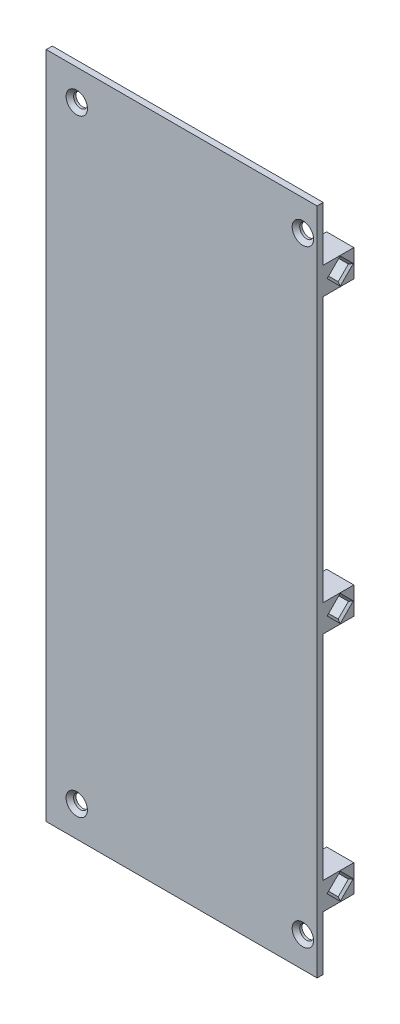
SolidWorks part; units mm, degrees
ref_plane "Front Plane" through (0, 0, 0) normal (0, 0, 1) x (1, 0, 0)
ref_plane "Top Plane" through (0, 0, 0) normal (0, 1, 0) x (1, 0, 0)
ref_plane "Right Plane" through (0, 0, 0) normal (1, 0, 0) x (0, 0, -1)
sketch "Sketch1" plane through (0, 0, 0) normal (0, 0, 1) x (1, 0, 0)
  line L1 (-42.2005, 104.14) -> (42.2005, 104.14)
  line L2 (-42.2005, 104.14) -> (-42.2005, -104.14)
  line L3 (-42.2005, -104.14) -> (42.2005, -104.14)
  line L4 (42.2005, 104.14) -> (42.2005, -104.14)
  point P4 (0, 104.14)
  point P6 (-42.2005, 0)
  dimension "D1" = 84.401
  dimension "D2" = 208.28
extrude "Boss-Extrude1" add sketch "Sketch1" along normal blind 1.905
sketch "Sketch2" plane through (0, 0, 1.905) normal (0, 0, 1) x (1, 0, 0)
  line L0 (-42.2005, -94.615) -> (-32.6755, -94.615) construction
  line L1 (-42.2005, 104.14) -> (-42.2005, -104.14) construction
  line L2 (-32.6755, -94.615) -> (-32.6755, -104.14) construction
  line L3 (-42.2005, -104.14) -> (42.2005, -104.14) construction
  line L4 (-42.2005, 94.615) -> (-32.6755, 94.615) construction
  line L5 (-32.6755, 94.615) -> (-32.6755, 104.14) construction
  line L6 (42.2005, 104.14) -> (-42.2005, 104.14) construction
  line L7 (42.2005, -104.14) -> (42.2005, 104.14) construction
  line L8 (37.7555, 94.615) -> (37.7555, 104.14) construction
  line L9 (37.7555, -94.615) -> (37.7555, -104.14) construction
  line L10 (37.7555, 94.615) -> (42.2005, 94.615) construction
  line L11 (37.7555, -94.615) -> (42.2005, -94.615) construction
  point P0 (-32.6755, 94.615)
  point P1 (-32.6755, -94.615)
  point P11 (37.7555, -94.615)
  point P15 (37.7555, 94.615)
  dimension "D1" = 4.445
  dimension "D2" = 9.525
hole_wizard "#6 Clearance Hole1" positions "Sketch2" profile "Sketch3" hole size "#6" standard "ANSI Inch" end condition up to next
sketch "Sketch3" plane through (-32.6755, 94.615, 1.905) normal (1, 0, 0) x (0, -1, 0)
  line L0 (0, 0) -> (0, 1.905)
  line L1 (0, 1.905) -> (2.1526, 1.905)
  line L2 (2.1526, 1.905) -> (2.1526, 1.1748)
  line L3 (2.1526, 1.1748) -> (3.3274, 0)
  line L5 (3.3274, 0) -> (0, 0)
  line L6 (-2.1526, 1.1747) -> (-3.3274, 0) construction
  line L11 (0, -6.35) -> (0, 107.95) construction
  dimension "Thru Hole Dia." = 4.3053
  dimension "Thru Hole Depth" = 1.905
  dimension "Near C'Sink Dia." = 6.6548
  dimension "Near C'Sink Angle" = 90
sketch "Sketch4" plane through (0, 0, 0) normal (0, 0, -1) x (-1, 0, 0)
  line L0 (-42.2005, -104.14) -> (-42.2005, 104.14) construction
  line L1 (-42.2005, 87.2067) -> (-33.7338, 87.2067)
  line L2 (-42.2005, 87.2067) -> (-42.2005, 78.74)
  line L3 (-42.2005, 78.74) -> (-33.7338, 78.74)
  line L4 (-33.7338, 87.2067) -> (-33.7338, 78.74)
  line L5 (-42.2005, 104.14) -> (42.2005, 104.14) construction
  line L6 (-42.2005, -3.81) -> (-33.7338, -3.81)
  line L7 (-42.2005, -3.81) -> (-42.2005, -12.2767)
  line L8 (-42.2005, -12.2767) -> (-33.7338, -12.2767)
  line L9 (-33.7338, -3.81) -> (-33.7338, -12.2767)
  line L10 (-42.2005, -78.74) -> (-33.7338, -78.74)
  line L11 (-42.2005, -78.74) -> (-42.2005, -87.2067)
  line L12 (-42.2005, -87.2067) -> (-33.7338, -87.2067)
  line L13 (-33.7338, -78.74) -> (-33.7338, -87.2067)
  line L14 (42.2005, -104.14) -> (-42.2005, -104.14) construction
  dimension "D1" = 8.4667
  dimension "D2" = 16.9333
  dimension "D3" = 16.9333
  dimension "D4" = 107.95
extrude "Boss-Extrude2" add sketch "Sketch4" along normal blind 9.525
sketch "Sketch5" plane through (42.2005, 0, 0) normal (1, 0, 0) x (0, 0, -1)
  line L0 (2.1167, -82.9733) -> (5.2917, -79.7983)
  line L1 (2.1167, -82.9733) -> (5.2917, -86.1483)
  line L2 (5.2917, -79.7983) -> (8.4667, -82.9733)
  line L3 (5.2917, -86.1483) -> (8.4667, -82.9733)
  line L4 (2.1167, -82.9733) -> (8.4667, -82.9733) construction
  line L5 (5.2917, -79.7983) -> (5.2917, -86.1483) construction
  line L6 (2.1167, -8.0433) -> (5.2917, -4.8683)
  line L7 (2.1167, -8.0433) -> (5.2917, -11.2183)
  line L8 (5.2917, -4.8683) -> (8.4667, -8.0433)
  line L9 (5.2917, -11.2183) -> (8.4667, -8.0433)
  line L10 (2.1167, -8.0433) -> (8.4667, -8.0433) construction
  line L11 (5.2917, -4.8683) -> (5.2917, -11.2183) construction
  line L12 (2.1167, 82.9733) -> (5.2917, 86.1483)
  line L13 (2.1167, 82.9733) -> (5.2917, 79.7983)
  line L14 (5.2917, 86.1483) -> (8.4667, 82.9733)
  line L15 (5.2917, 79.7983) -> (8.4667, 82.9733)
  line L16 (2.1167, 82.9733) -> (8.4667, 82.9733) construction
  line L17 (5.2917, 86.1483) -> (5.2917, 79.7983) construction
  line L18 (9.525, 87.2067) -> (9.525, 78.74) construction
  line L19 (9.525, -78.74) -> (9.525, -87.2067) construction
  line L20 (9.525, -3.81) -> (9.525, -12.2767) construction
  point P1 (5.2917, -82.9733)
  point P2 (5.2917, -8.0433)
  point P3 (5.2917, 82.9733)
  point P13 (9.525, 82.9733)
  point P20 (9.525, -82.9733)
  point P23 (9.525, -8.0433)
  dimension "D1" = 4.2333
  dimension "D2" = 6.35
extrude "Cut-Extrude3" cut sketch "Sketch5" against normal blind 6.35
chamfer "Chamfer1" distance 0.635 angle 45 20 edges at (35.8505, -81.3858, -3.7042) (35.8505, -81.3858, -6.8792) (35.8505, -84.5608, -6.8792) (35.8505, -84.5608, -3.7042) (35.8505, 84.5608, -3.7042) (35.8505, 84.5608, -6.8792) (35.8505, 81.3858, -6.8792) (35.8505, 81.3858, -3.7042) (42.2005, -84.5608, -3.7042) (42.2005, -84.5608, -6.8792) (42.2005, -81.3858, -6.8792) (42.2005, -81.3858, -3.7042) (42.2005, -9.6308, -3.7042) (42.2005, -9.6308, -6.8792) (42.2005, -6.4558, -6.8792) (42.2005, -6.4558, -3.7042) (42.2005, 81.3858, -3.7042) (42.2005, 81.3858, -6.8792) (42.2005, 84.5608, -6.8792) (42.2005, 84.5608, -3.7042)
